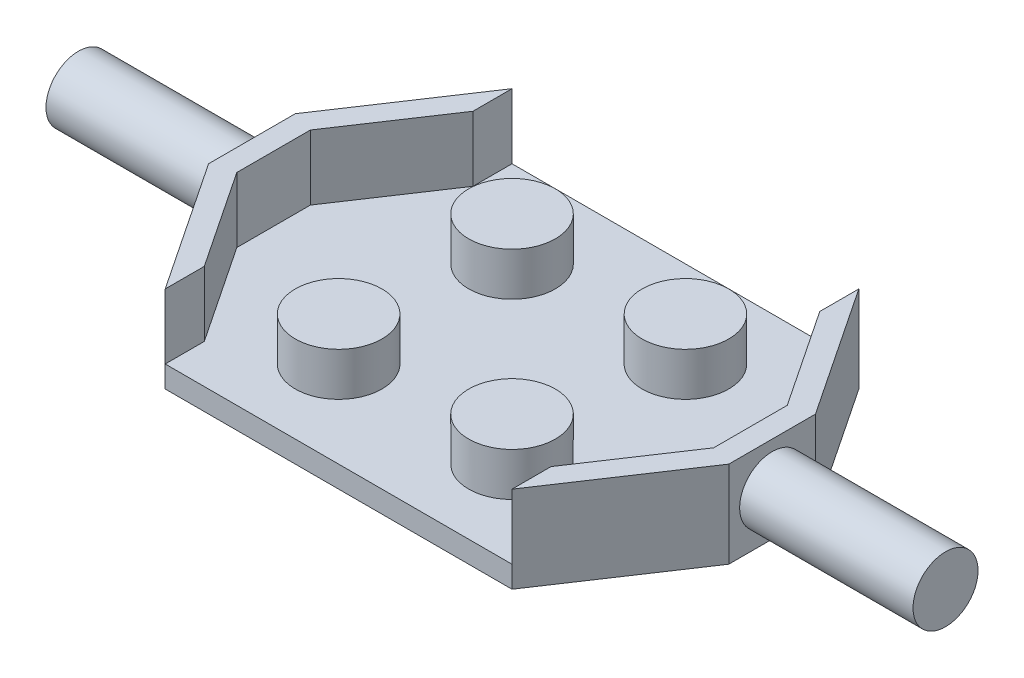
SolidWorks part; units mm, degrees
ref_plane "Front Plane" through (0, 0, 0) normal (0, 0, 1) x (1, 0, 0)
ref_plane "Top Plane" through (0, 0, 0) normal (0, 1, 0) x (1, 0, 0)
ref_plane "Right Plane" through (0, 0, 0) normal (1, 0, 0) x (0, 0, -1)
sketch "Sketch1" plane through (0, 0, 0) normal (0, 1, 0) x (1, 0, 0)
  line L0 (0, 0) -> (-12, 0) construction
  line L1 (-12, -2) -> (-12, 2)
  line L2 (-12, 2) -> (-8, 8)
  line L3 (-8, 8) -> (0, 8)
  line L4 (0, 8) -> (0, -8)
  line L5 (-8, -8) -> (0, -8)
  line L6 (-12, -2) -> (-8, -8)
  dimension "D1" = 12
  dimension "D2" = 8
  dimension "D3" = 8
  dimension "D4" = 2
extrude "Boss-Extrude1" add sketch "Sketch1" along normal blind 1
sketch "Sketch2" plane through (0, 1, 0) normal (0, 1, 0) x (1, 0, 0)
  line L0 (0, 0) -> (-12, 0) construction
  line L1 (-12, 2) -> (-12, -2) construction
  line L2 (0, -8) -> (0, 8) construction
  line L3 (0, 8) -> (-8, 8) construction
  circle A0 centre (-4, 4) radius 2
  circle A1 centre (-4, -4) radius 2
  point P9 (0, 0)
  point P11 (0, 4.7092)
  dimension "D1" = 4
  dimension "D2" = 4
  dimension "D3" = 4
extrude "Boss-Extrude2" add sketch "Sketch2" along normal blind 2
sketch "Sketch3" plane through (0, 1, 0) normal (0, 1, 0) x (1, 0, 0)
  line L0 (-8, 8) -> (-12, 2) construction
  line L1 (-12, 2) -> (-12, -2) construction
  line L2 (-12, -2) -> (-8, -8) construction
  line L3 (-12, -2) -> (-8, -8)
  line L4 (-12, 2) -> (-12, -2)
  line L5 (-8, 8) -> (-12, 2)
  line L6 (-8, 6.1972) -> (-11, 1.6972)
  line L7 (-11, 1.6972) -> (-11, -1.6972)
  line L8 (-11, -1.6972) -> (-8, -6.1972)
  line L9 (-8, 8) -> (-8, 6.1972)
  line L10 (-8, -6.1972) -> (-8, -8)
  line L11 (-7.1679, 7.4453) -> (-11, 1.6972) construction
  line L12 (-11, -1.6972) -> (-7.1679, -7.4453) construction
  dimension "D1" = 1
extrude "Boss-Extrude3" add sketch "Sketch3" along normal blind 3
sketch "Sketch4" plane through (-12, 0, 0) normal (-1, 0, 0) x (0, 0, 1)
  line L0 (0, 0) -> (0, 4) construction
  line L1 (-2, 4) -> (2, 4) construction
  circle A0 centre (0, 2) radius 1.5
  point P8 (0, 2)
  dimension "D1" = 3
extrude "Boss-Extrude4" add sketch "Sketch4" along normal blind 8
mirror "Mirror1" about plane through (0, 0, 0) normal (1, 0, 0) of "Boss-Extrude4", "Boss-Extrude1", "Boss-Extrude2", "Boss-Extrude3"
